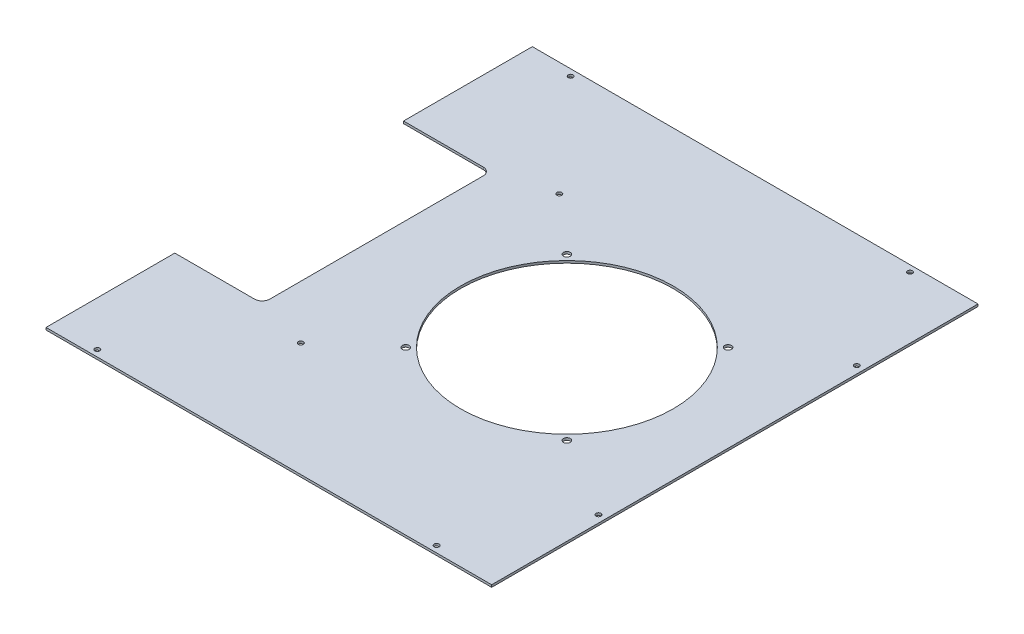
SolidWorks part; units mm, degrees
ref_plane "정면" through (0, 0, 0) normal (0, 0, 1) x (1, 0, 0)
ref_plane "윗면" through (0, 0, 0) normal (0, 1, 0) x (1, 0, 0)
ref_plane "우측면" through (0, 0, 0) normal (1, 0, 0) x (0, 0, -1)
sketch "스케치1" plane through (0, 0, 0) normal (0, 1, 0) x (1, 0, 0)
  line L1 (0, 0) -> (586.5, 0)
  line L2 (0, 0) -> (0, 640)
  line L3 (0, 640) -> (586.5, 640)
  line L4 (586.5, 0) -> (586.5, 640)
  dimension "D1" = 640
  dimension "D2" = 586.5
extrude "보스-돌출1" add sketch "스케치1" along normal blind 3
sketch "스케치2" plane through (0, 3, 0) normal (0, 1, 0) x (1, 0, 0)
  line L0 (0, 640) -> (0, 0) construction
  line L1 (0, 470.5) -> (105, 470.5)
  line L2 (0, 470.5) -> (0, 169.5)
  line L3 (0, 169.5) -> (105, 169.5)
  line L4 (115, 460.5) -> (115, 179.5)
  line L5 (586.5, 320) -> (0, 320) construction
  line L6 (586.5, 0) -> (586.5, 640) construction
  arc A0 (105, 169.5) -> (115, 179.5) centre (105, 179.5) ccw
  arc A1 (105, 470.5) -> (115, 460.5) centre (105, 460.5) cw
  dimension "D3" = 10
  dimension "D1" = 301
  dimension "D2" = 115
extrude "컷-돌출1" cut sketch "스케치2" against normal blind 3
sketch "스케치3" plane through (0, 3, 0) normal (0, 1, 0) x (1, 0, 0)
  line L1 (586.5, 320) -> (115, 320) construction
  line L2 (586.5, 0) -> (586.5, 640) construction
  line L3 (115, 179.5) -> (115, 460.5) construction
  line L5 (0, 640) -> (0, 470.5) construction
  circle A0 centre (365.5, 320) radius 140
  dimension "D1" = 280
  dimension "D2" = 365.5
extrude "컷-돌출2" cut sketch "스케치3" against normal blind 3
sketch "스케치4" plane through (0, 3, 0) normal (0, 1, 0) x (1, 0, 0)
  line L0 (259.434, 426.066) -> (471.566, 213.934) construction
  line L2 (471.566, 426.066) -> (259.434, 213.934) construction
  line L3 (365.5, 470) -> (365.5, 170) construction
  circle A0 centre (365.5, 320) radius 150 construction
  circle A1 centre (259.434, 426.066) radius 4.5
  circle A2 centre (471.566, 426.066) radius 4.5
  circle A3 centre (471.566, 213.934) radius 4.5
  circle A4 centre (259.434, 213.934) radius 4.5
  dimension "D1" = 300
  dimension "D4" = 9
  dimension "D2" = 45
  dimension "D3" = 45
extrude "컷-돌출3" cut sketch "스케치4" against normal through all
sketch "스케치5" plane through (0, 3, 0) normal (0, 1, 0) x (1, 0, 0)
  line L0 (586.5, 320) -> (13.9408, 320) construction
  line L1 (586.5, 0) -> (586.5, 640) construction
  line L2 (586.5, 640) -> (0, 640) construction
  line L3 (0, 640) -> (0, 470.5) construction
  circle A0 centre (59, 631.5) radius 3.25
  circle A1 centre (505.5, 631.5) radius 3.25
  circle A2 centre (185.5, 490) radius 3.25
  circle A3 centre (577, 490) radius 3.25
  circle A4 centre (577, 150) radius 3.25
  circle A5 centre (185.5, 150) radius 3.25
  circle A6 centre (505.5, 8.5) radius 3.25
  circle A7 centre (59, 8.5) radius 3.25
  point P0 (59, 631.5)
  point P1 (505.5, 631.5)
  point P2 (185.5, 490)
  point P3 (577, 490)
  point P14 (577, 150)
  point P15 (185.5, 150)
  point P16 (505.5, 8.5)
  point P17 (59, 8.5)
  point P36 (577, 150)
  point P37 (185.5, 150)
  point P38 (505.5, 8.5)
  point P39 (59, 8.5)
  dimension "D7" = 6.5
  dimension "D1" = 170
  dimension "D2" = 8.5
  dimension "D3" = 59
  dimension "D4" = 126.5
  dimension "D5" = 320
  dimension "D6" = 71.5
extrude "컷-돌출4" cut sketch "스케치5" against normal through all
